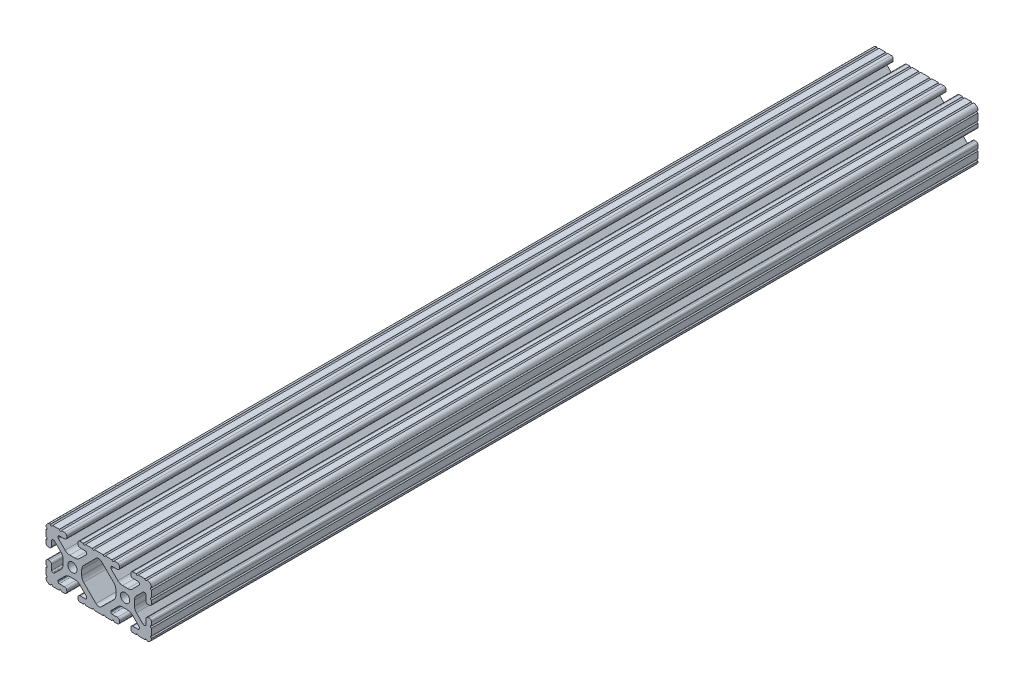
SolidWorks part; units mm, degrees
material "6105-T5 Aluminum"
ref_plane "Front Plane" through (0, 0, 0) normal (0, 0, 1) x (1, 0, 0)
ref_plane "Top Plane" through (0, 0, 0) normal (0, 1, 0) x (1, 0, 0)
ref_plane "Right Plane" through (0, 0, 0) normal (1, 0, 0) x (0, 0, -1)
sketch "Sketch1" plane through (0, 0, 0) normal (0, 0, 1) x (1, 0, 0)
  line L0 (-12.312, -1.8969) -> (-12.312, 1.8969)
  line L1 (-10.9208, 5.2555) -> (-2.0655, 14.1109)
  line L2 (2.0655, 14.1109) -> (10.9208, 5.2555)
  line L3 (12.312, 1.8969) -> (12.312, -1.8969)
  line L4 (10.9208, -5.2555) -> (2.0655, -14.1109)
  line L5 (-2.0655, -14.1109) -> (-10.9208, -5.2555)
  line L6 (38.1, -14.3256) -> (38.1, -9.4996)
  line L7 (38.1, -7.9756) -> (38.1, -5.6388)
  line L8 (36.5252, -4.064) -> (35.6108, -4.064)
  line L9 (34.036, -5.6388) -> (34.036, -9.398)
  line L10 (33.147, -10.287) -> (32.5789, -10.287)
  line L11 (31.9503, -10.0266) -> (27.1792, -5.2555)
  line L12 (25.788, -1.8969) -> (25.788, 1.8969)
  line L13 (27.1792, 5.2555) -> (31.9503, 10.0266)
  line L14 (32.5789, 10.287) -> (33.147, 10.287)
  line L15 (34.036, 9.398) -> (34.036, 5.6388)
  line L16 (35.6108, 4.064) -> (36.5252, 4.064)
  line L17 (38.1, 5.6388) -> (38.1, 7.9756)
  line L18 (38.1, 9.4996) -> (38.1, 14.3256)
  line L19 (38.1, 15.8496) -> (38.1, 15.875)
  line L20 (34.925, 19.05) -> (34.8996, 19.05)
  line L21 (33.3756, 19.05) -> (28.5496, 19.05)
  line L22 (27.0256, 19.05) -> (24.6888, 19.05)
  line L23 (23.114, 17.4752) -> (23.114, 16.5608)
  line L24 (24.6888, 14.986) -> (28.448, 14.986)
  line L25 (29.337, 14.097) -> (29.337, 13.5289)
  line L26 (29.0766, 12.9003) -> (24.3055, 8.1292)
  line L27 (20.9469, 6.738) -> (17.1531, 6.738)
  line L28 (13.7945, 8.1292) -> (9.0234, 12.9003)
  line L29 (8.763, 13.5289) -> (8.763, 14.097)
  line L30 (9.652, 14.986) -> (13.4112, 14.986)
  line L31 (14.986, 16.5608) -> (14.986, 17.4752)
  line L32 (13.4112, 19.05) -> (11.0744, 19.05)
  line L33 (9.5504, 19.05) -> (4.7244, 19.05)
  line L34 (3.2004, 19.05) -> (-3.2004, 19.05)
  line L35 (-4.7244, 19.05) -> (-9.5504, 19.05)
  line L36 (-11.0744, 19.05) -> (-13.4112, 19.05)
  line L37 (-14.986, 17.4752) -> (-14.986, 16.5608)
  line L38 (-13.4112, 14.986) -> (-9.652, 14.986)
  line L39 (-8.763, 14.097) -> (-8.763, 13.5289)
  line L40 (-9.0234, 12.9003) -> (-13.7945, 8.1292)
  line L41 (-17.1531, 6.738) -> (-20.9469, 6.738)
  line L42 (-24.3055, 8.1292) -> (-29.0766, 12.9003)
  line L43 (-29.337, 13.5289) -> (-29.337, 14.097)
  line L44 (-28.448, 14.986) -> (-24.6888, 14.986)
  line L45 (-23.114, 16.5608) -> (-23.114, 17.4752)
  line L46 (-24.6888, 19.05) -> (-27.0256, 19.05)
  line L47 (-28.5496, 19.05) -> (-33.3756, 19.05)
  line L48 (-34.8996, 19.05) -> (-34.925, 19.05)
  line L49 (-38.1, 15.875) -> (-38.1, 15.8496)
  line L50 (-38.1, 14.3256) -> (-38.1, 9.4996)
  line L51 (-38.1, 7.9756) -> (-38.1, 5.6388)
  line L52 (-36.5252, 4.064) -> (-35.6108, 4.064)
  line L53 (-34.036, 5.6388) -> (-34.036, 9.398)
  line L54 (-33.147, 10.287) -> (-32.5789, 10.287)
  line L55 (-31.9503, 10.0266) -> (-27.1792, 5.2555)
  line L56 (-25.788, 1.8969) -> (-25.788, -1.8969)
  line L57 (-27.1792, -5.2555) -> (-31.9503, -10.0266)
  line L58 (-32.5789, -10.287) -> (-33.147, -10.287)
  line L59 (-34.036, -9.398) -> (-34.036, -5.6388)
  line L60 (-35.6108, -4.064) -> (-36.5252, -4.064)
  line L61 (-38.1, -5.6388) -> (-38.1, -7.9756)
  line L62 (-38.1, -9.4996) -> (-38.1, -14.3256)
  line L63 (-38.1, -15.8496) -> (-38.1, -15.875)
  line L64 (-34.925, -19.05) -> (-34.8996, -19.05)
  line L65 (-33.3756, -19.05) -> (-28.5496, -19.05)
  line L66 (-27.0256, -19.05) -> (-24.6888, -19.05)
  line L67 (-23.114, -17.4752) -> (-23.114, -16.5608)
  line L68 (-24.6888, -14.986) -> (-28.448, -14.986)
  line L69 (-29.337, -14.097) -> (-29.337, -13.5289)
  line L70 (-29.0766, -12.9003) -> (-24.3055, -8.1292)
  line L71 (-20.9469, -6.738) -> (-17.1531, -6.738)
  line L72 (-13.7945, -8.1292) -> (-9.0234, -12.9003)
  line L73 (-8.763, -13.5289) -> (-8.763, -14.097)
  line L74 (-9.652, -14.986) -> (-13.4112, -14.986)
  line L75 (-14.986, -16.5608) -> (-14.986, -17.4752)
  line L76 (-13.4112, -19.05) -> (-11.0744, -19.05)
  line L77 (-9.5504, -19.05) -> (-4.7244, -19.05)
  line L78 (-3.2004, -19.05) -> (3.2004, -19.05)
  line L79 (4.7244, -19.05) -> (9.5504, -19.05)
  line L80 (11.0744, -19.05) -> (13.4112, -19.05)
  line L81 (14.986, -17.4752) -> (14.986, -16.5608)
  line L82 (13.4112, -14.986) -> (9.652, -14.986)
  line L83 (8.763, -14.097) -> (8.763, -13.5289)
  line L84 (9.0234, -12.9003) -> (13.7945, -8.1292)
  line L85 (17.1531, -6.738) -> (20.9469, -6.738)
  line L86 (24.3055, -8.1292) -> (29.0766, -12.9003)
  line L87 (29.337, -13.5289) -> (29.337, -14.097)
  line L88 (28.448, -14.986) -> (24.6888, -14.986)
  line L89 (23.114, -16.5608) -> (23.114, -17.4752)
  line L90 (24.6888, -19.05) -> (27.0256, -19.05)
  line L91 (28.5496, -19.05) -> (33.3756, -19.05)
  line L92 (34.8996, -19.05) -> (34.925, -19.05)
  line L93 (38.1, -15.875) -> (38.1, -15.8496)
  circle A0 centre (19.05, 0) radius 3.3274
  circle A1 centre (-19.05, 0) radius 3.3274
  arc A2 (-10.9208, 5.2555) -> (-12.312, 1.8969) centre (-7.5622, 1.8969) ccw
  arc A3 (2.0655, 14.1109) -> (-2.0655, 14.1109) centre (0, 12.0454) ccw
  arc A4 (12.312, 1.8969) -> (10.9208, 5.2555) centre (7.5622, 1.8969) ccw
  arc A5 (10.9208, -5.2555) -> (12.312, -1.8969) centre (7.5622, -1.8969) ccw
  arc A6 (-2.0655, -14.1109) -> (2.0655, -14.1109) centre (0, -12.0454) ccw
  arc A7 (-12.312, -1.8969) -> (-10.9208, -5.2555) centre (-7.5622, -1.8969) ccw
  arc A8 (38.1, -14.3256) -> (38.1, -15.8496) centre (38.1, -15.0876) ccw
  arc A9 (38.1, -7.9756) -> (38.1, -9.4996) centre (38.1, -8.7376) ccw
  arc A10 (38.1, -5.6388) -> (36.5252, -4.064) centre (36.5252, -5.6388) ccw
  arc A11 (35.6108, -4.064) -> (34.036, -5.6388) centre (35.6108, -5.6388) ccw
  arc A12 (33.147, -10.287) -> (34.036, -9.398) centre (33.147, -9.398) ccw
  arc A13 (31.9503, -10.0266) -> (32.5789, -10.287) centre (32.5789, -9.398) ccw
  arc A14 (25.788, -1.8969) -> (27.1792, -5.2555) centre (30.5378, -1.8969) ccw
  arc A15 (27.1792, 5.2555) -> (25.788, 1.8969) centre (30.5378, 1.8969) ccw
  arc A16 (32.5789, 10.287) -> (31.9503, 10.0266) centre (32.5789, 9.398) ccw
  arc A17 (34.036, 9.398) -> (33.147, 10.287) centre (33.147, 9.398) ccw
  arc A18 (34.036, 5.6388) -> (35.6108, 4.064) centre (35.6108, 5.6388) ccw
  arc A19 (36.5252, 4.064) -> (38.1, 5.6388) centre (36.5252, 5.6388) ccw
  arc A20 (38.1, 9.4996) -> (38.1, 7.9756) centre (38.1, 8.7376) ccw
  arc A21 (38.1, 15.8496) -> (38.1, 14.3256) centre (38.1, 15.0876) ccw
  arc A22 (38.1, 15.875) -> (34.925, 19.05) centre (34.925, 15.875) ccw
  arc A23 (33.3756, 19.05) -> (34.8996, 19.05) centre (34.1376, 19.05) ccw
  arc A24 (27.0256, 19.05) -> (28.5496, 19.05) centre (27.7876, 19.05) ccw
  arc A25 (24.6888, 19.05) -> (23.114, 17.4752) centre (24.6888, 17.4752) ccw
  arc A26 (23.114, 16.5608) -> (24.6888, 14.986) centre (24.6888, 16.5608) ccw
  arc A27 (29.337, 14.097) -> (28.448, 14.986) centre (28.448, 14.097) ccw
  arc A28 (29.0766, 12.9003) -> (29.337, 13.5289) centre (28.448, 13.5289) ccw
  arc A29 (20.9469, 6.738) -> (24.3055, 8.1292) centre (20.9469, 11.4878) ccw
  arc A30 (13.7945, 8.1292) -> (17.1531, 6.738) centre (17.1531, 11.4878) ccw
  arc A31 (8.763, 13.5289) -> (9.0234, 12.9003) centre (9.652, 13.5289) ccw
  arc A32 (9.652, 14.986) -> (8.763, 14.097) centre (9.652, 14.097) ccw
  arc A33 (13.4112, 14.986) -> (14.986, 16.5608) centre (13.4112, 16.5608) ccw
  arc A34 (14.986, 17.4752) -> (13.4112, 19.05) centre (13.4112, 17.4752) ccw
  arc A35 (9.5504, 19.05) -> (11.0744, 19.05) centre (10.3124, 19.05) ccw
  arc A36 (3.2004, 19.05) -> (4.7244, 19.05) centre (3.9624, 19.05) ccw
  arc A37 (-4.7244, 19.05) -> (-3.2004, 19.05) centre (-3.9624, 19.05) ccw
  arc A38 (-11.0744, 19.05) -> (-9.5504, 19.05) centre (-10.3124, 19.05) ccw
  arc A39 (-13.4112, 19.05) -> (-14.986, 17.4752) centre (-13.4112, 17.4752) ccw
  arc A40 (-14.986, 16.5608) -> (-13.4112, 14.986) centre (-13.4112, 16.5608) ccw
  arc A41 (-8.763, 14.097) -> (-9.652, 14.986) centre (-9.652, 14.097) ccw
  arc A42 (-9.0234, 12.9003) -> (-8.763, 13.5289) centre (-9.652, 13.5289) ccw
  arc A43 (-17.1531, 6.738) -> (-13.7945, 8.1292) centre (-17.1531, 11.4878) ccw
  arc A44 (-24.3055, 8.1292) -> (-20.9469, 6.738) centre (-20.9469, 11.4878) ccw
  arc A45 (-29.337, 13.5289) -> (-29.0766, 12.9003) centre (-28.448, 13.5289) ccw
  arc A46 (-28.448, 14.986) -> (-29.337, 14.097) centre (-28.448, 14.097) ccw
  arc A47 (-24.6888, 14.986) -> (-23.114, 16.5608) centre (-24.6888, 16.5608) ccw
  arc A48 (-23.114, 17.4752) -> (-24.6888, 19.05) centre (-24.6888, 17.4752) ccw
  arc A49 (-28.5496, 19.05) -> (-27.0256, 19.05) centre (-27.7876, 19.05) ccw
  arc A50 (-34.8996, 19.05) -> (-33.3756, 19.05) centre (-34.1376, 19.05) ccw
  arc A51 (-34.925, 19.05) -> (-38.1, 15.875) centre (-34.925, 15.875) ccw
  arc A52 (-38.1, 14.3256) -> (-38.1, 15.8496) centre (-38.1, 15.0876) ccw
  arc A53 (-38.1, 7.9756) -> (-38.1, 9.4996) centre (-38.1, 8.7376) ccw
  arc A54 (-38.1, 5.6388) -> (-36.5252, 4.064) centre (-36.5252, 5.6388) ccw
  arc A55 (-35.6108, 4.064) -> (-34.036, 5.6388) centre (-35.6108, 5.6388) ccw
  arc A56 (-33.147, 10.287) -> (-34.036, 9.398) centre (-33.147, 9.398) ccw
  arc A57 (-31.9503, 10.0266) -> (-32.5789, 10.287) centre (-32.5789, 9.398) ccw
  arc A58 (-25.788, 1.8969) -> (-27.1792, 5.2555) centre (-30.5378, 1.8969) ccw
  arc A59 (-27.1792, -5.2555) -> (-25.788, -1.8969) centre (-30.5378, -1.8969) ccw
  arc A60 (-32.5789, -10.287) -> (-31.9503, -10.0266) centre (-32.5789, -9.398) ccw
  arc A61 (-34.036, -9.398) -> (-33.147, -10.287) centre (-33.147, -9.398) ccw
  arc A62 (-34.036, -5.6388) -> (-35.6108, -4.064) centre (-35.6108, -5.6388) ccw
  arc A63 (-36.5252, -4.064) -> (-38.1, -5.6388) centre (-36.5252, -5.6388) ccw
  arc A64 (-38.1, -9.4996) -> (-38.1, -7.9756) centre (-38.1, -8.7376) ccw
  arc A65 (-38.1, -15.8496) -> (-38.1, -14.3256) centre (-38.1, -15.0876) ccw
  arc A66 (-38.1, -15.875) -> (-34.925, -19.05) centre (-34.925, -15.875) ccw
  arc A67 (-33.3756, -19.05) -> (-34.8996, -19.05) centre (-34.1376, -19.05) ccw
  arc A68 (-27.0256, -19.05) -> (-28.5496, -19.05) centre (-27.7876, -19.05) ccw
  arc A69 (-24.6888, -19.05) -> (-23.114, -17.4752) centre (-24.6888, -17.4752) ccw
  arc A70 (-23.114, -16.5608) -> (-24.6888, -14.986) centre (-24.6888, -16.5608) ccw
  arc A71 (-29.337, -14.097) -> (-28.448, -14.986) centre (-28.448, -14.097) ccw
  arc A72 (-29.0766, -12.9003) -> (-29.337, -13.5289) centre (-28.448, -13.5289) ccw
  arc A73 (-20.9469, -6.738) -> (-24.3055, -8.1292) centre (-20.9469, -11.4878) ccw
  arc A74 (-13.7945, -8.1292) -> (-17.1531, -6.738) centre (-17.1531, -11.4878) ccw
  arc A75 (-8.763, -13.5289) -> (-9.0234, -12.9003) centre (-9.652, -13.5289) ccw
  arc A76 (-9.652, -14.986) -> (-8.763, -14.097) centre (-9.652, -14.097) ccw
  arc A77 (-13.4112, -14.986) -> (-14.986, -16.5608) centre (-13.4112, -16.5608) ccw
  arc A78 (-14.986, -17.4752) -> (-13.4112, -19.05) centre (-13.4112, -17.4752) ccw
  arc A79 (-9.5504, -19.05) -> (-11.0744, -19.05) centre (-10.3124, -19.05) ccw
  arc A80 (-3.2004, -19.05) -> (-4.7244, -19.05) centre (-3.9624, -19.05) ccw
  arc A81 (4.7244, -19.05) -> (3.2004, -19.05) centre (3.9624, -19.05) ccw
  arc A82 (11.0744, -19.05) -> (9.5504, -19.05) centre (10.3124, -19.05) ccw
  arc A83 (13.4112, -19.05) -> (14.986, -17.4752) centre (13.4112, -17.4752) ccw
  arc A84 (14.986, -16.5608) -> (13.4112, -14.986) centre (13.4112, -16.5608) ccw
  arc A85 (8.763, -14.097) -> (9.652, -14.986) centre (9.652, -14.097) ccw
  arc A86 (9.0234, -12.9003) -> (8.763, -13.5289) centre (9.652, -13.5289) ccw
  arc A87 (17.1531, -6.738) -> (13.7945, -8.1292) centre (17.1531, -11.4878) ccw
  arc A88 (24.3055, -8.1292) -> (20.9469, -6.738) centre (20.9469, -11.4878) ccw
  arc A89 (29.337, -13.5289) -> (29.0766, -12.9003) centre (28.448, -13.5289) ccw
  arc A90 (28.448, -14.986) -> (29.337, -14.097) centre (28.448, -14.097) ccw
  arc A91 (24.6888, -14.986) -> (23.114, -16.5608) centre (24.6888, -16.5608) ccw
  arc A92 (23.114, -17.4752) -> (24.6888, -19.05) centre (24.6888, -17.4752) ccw
  arc A93 (28.5496, -19.05) -> (27.0256, -19.05) centre (27.7876, -19.05) ccw
  arc A94 (34.8996, -19.05) -> (33.3756, -19.05) centre (34.1376, -19.05) ccw
  arc A95 (34.925, -19.05) -> (38.1, -15.875) centre (34.925, -15.875) ccw
  dimension "D1" = 19.05
  dimension "D2" = 19.05
extrude "Boss-Extrude1" add sketch "Sketch1" along normal blind 596.9
